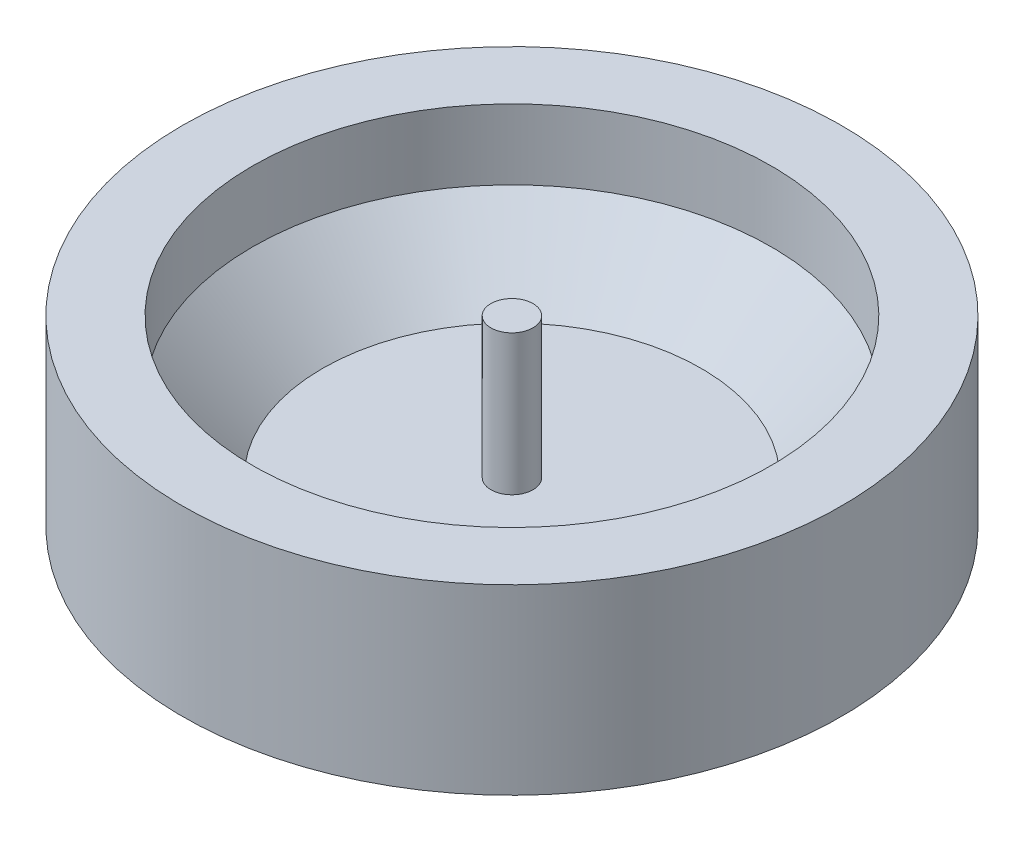
SolidWorks part; units mm, degrees
ref_plane "Plan de face" through (0, 0, 0) normal (0, 0, 1) x (1, 0, 0)
ref_plane "Plan de dessus" through (0, 0, 0) normal (0, 1, 0) x (1, 0, 0)
ref_plane "Plan de droite" through (0, 0, 0) normal (1, 0, 0) x (0, 0, -1)
sketch "Esquisse1" plane through (0, 0, 0) normal (0, 0, 1) x (1, 0, 0)
  line L11 (-13.5, 0) -> (0, 0) construction
  line L18 (0, 5) -> (0, 0) construction
  line L19 (-18.5, 5) -> (-18.5, 10)
  line L21 (0, 10) -> (0, 5) construction
  line L22 (-18.5, 5) -> (0, 5) construction
  line L24 (-13.5, 0) -> (-18.5, 5)
  line L25 (-18.5, 10) -> (-23.5, 10)
  line L26 (-23.5, 10) -> (-23.5, 0)
  line L27 (-23.5, 0) -> (-13.5, 0) construction
  line L28 (-23.5, 0) -> (-23.5, -3)
  line L29 (-23.5, -3) -> (0, -3)
  line L30 (0, -3) -> (0, 10)
  line L31 (0, 10) -> (-1.5, 10)
  line L32 (-1.5, 10) -> (-1.5, 0)
  line L33 (-1.5, 0) -> (-13.5, 0)
  dimension "D2" = 18.5
  dimension "D3" = 5
  dimension "D4" = 5
  dimension "D5" = 3
  dimension "D6" = 1.5
  dimension "D13" = 5
  dimension "D14" = 5
  dimension "D15" = 18.5
revolve "Révolution1" add sketch "Esquisse1" angle 360 about L21
